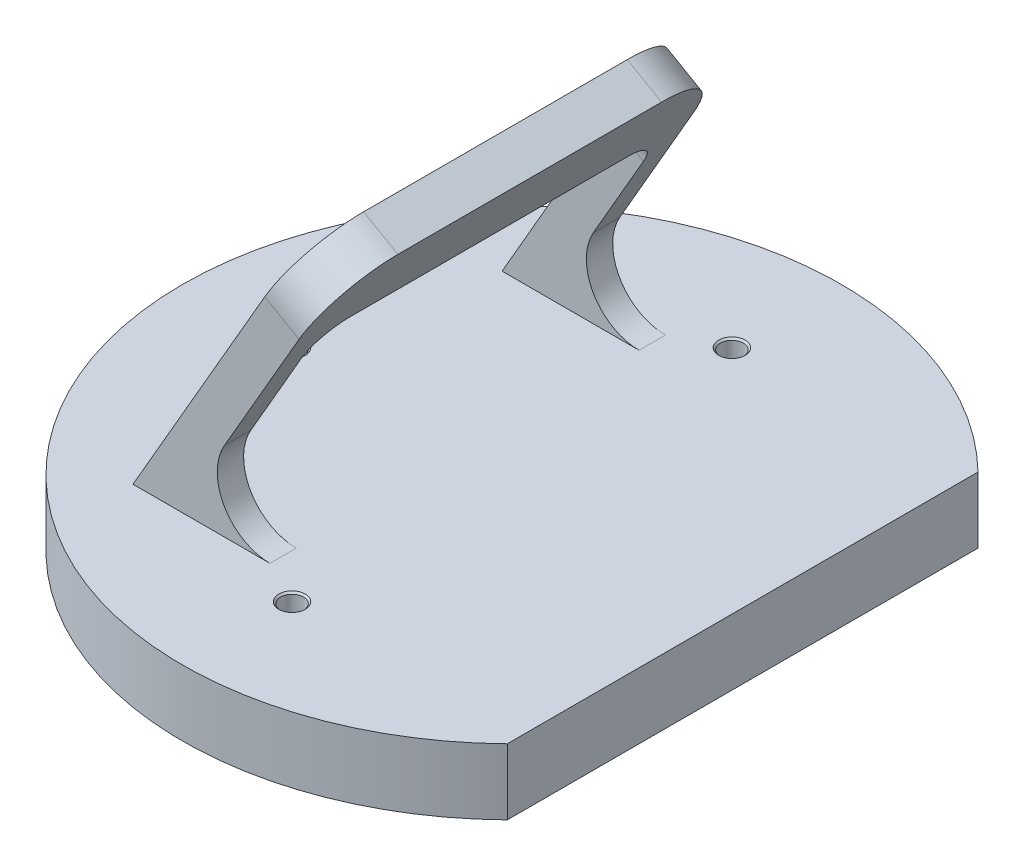
SolidWorks part; units mm, degrees
ref_plane "前视基准面" through (0, 0, 0) normal (0, 0, 1) x (1, 0, 0)
ref_plane "上视基准面" through (0, 0, 0) normal (0, 1, 0) x (1, 0, 0)
ref_plane "右视基准面" through (0, 0, 0) normal (1, 0, 0) x (0, 0, -1)
other "Configuration Table"
sketch "草图1" plane through (0, 0, 0) normal (0, 1, 0) x (1, 0, 0)
  line L0 (70, 71.4143) -> (70, -71.4143)
  arc A0 (70, 71.4143) -> (70, -71.4143) centre (0, 0) ccw
  dimension "D1" = 100
  dimension "D2" = 70
extrude "凸台-拉伸2" add sketch "草图1" along normal blind 20
sketch "草图5" plane through (0, 0, 0) normal (0, 0, 1) x (1, 0, 0)
  line L0 (-55, 20) -> (-5, 106.6025)
  line L1 (70, 20) -> (-100, 20) construction
  dimension "D1" = 100
  dimension "D2" = 60
  dimension "D3" = 55
extrude "拉伸-薄壁2" add sketch "草图5" along normal mid plane 120 thin
sketch "草图7" plane through (0, 0, 0) normal (0, 0, 1) x (1, 0, 0)
  line L0 (-17.5, 84.9519) -> (-7.1077, 78.9519)
  line L4 (-55, 20) -> (-41.1436, 20)
  line L5 (-41.1436, 20) -> (5.3923, 100.6025)
  line L6 (5.3923, 100.6025) -> (-5, 106.6025)
  line L7 (-5, 106.6025) -> (-55, 20)
  line L8 (-55, 20) -> (-41.1436, 20)
  line L9 (-41.1436, 20) -> (-7.1077, 78.9519)
  line L11 (-17.5, 84.9519) -> (-55, 20)
  dimension "D2" = 75
  dimension "D1" = 0
extrude "切除-拉伸2" cut sketch "草图7" against normal mid plane 104
fillet "圆角1" radius 20 2 edges at (0.1962, 103.6025, -60) (0.1962, 103.6025, 60)
fillet "圆角2" radius 10 2 edges at (-12.3038, 81.9519, 52) (-12.3038, 81.9519, -52)
fillet "圆角4" radius 16 1 edges at (-41.1436, 20, -56)
fillet "圆角5" radius 16 1 edges at (-41.1436, 20, 56)
sketch "草图8" plane through (0, 20, 0) normal (0, 1, 0) x (1, 0, 0)
  circle A0 centre (0, 0) radius 66.7379 construction
  point P3 (0, 66.7379)
  point P4 (0, -66.7379)
  point P6 (-66.7379, 0)
hole_wizard "M8x1.0 螺纹孔1" positions "草图8" profile "草图9" tap size "M8x1.0" standard "GB" end condition through all
sketch "草图9" plane through (-66.7379, 20, 0) normal (1, 0, 0) x (0, 0, 1)
  line L0 (0, 0) -> (0, 20)
  line L1 (0, 20) -> (3.5, 20)
  line L2 (3.5, 20) -> (3.5, 0.525)
  line L3 (3.5, 0.525) -> (4.025, 0)
  line L5 (4.025, 0) -> (0, 0)
  line L6 (-3.5, 0.525) -> (-4.025, 0) construction
  line L11 (0, -6.35) -> (0, 107.95) construction
  dimension "通孔螺纹孔钻头直径" = 7
  dimension "通孔螺纹孔钻头深度" = 20
  dimension "近端锥形沉头孔直径" = 8.05
  dimension "近端锥形沉头孔角度" = 90
cosmetic thread "孔螺纹线1" parameters "D2"=8
cosmetic thread "孔螺纹线2" parameters "D2"=8
cosmetic thread "孔螺纹线3" parameters "D2"=8
